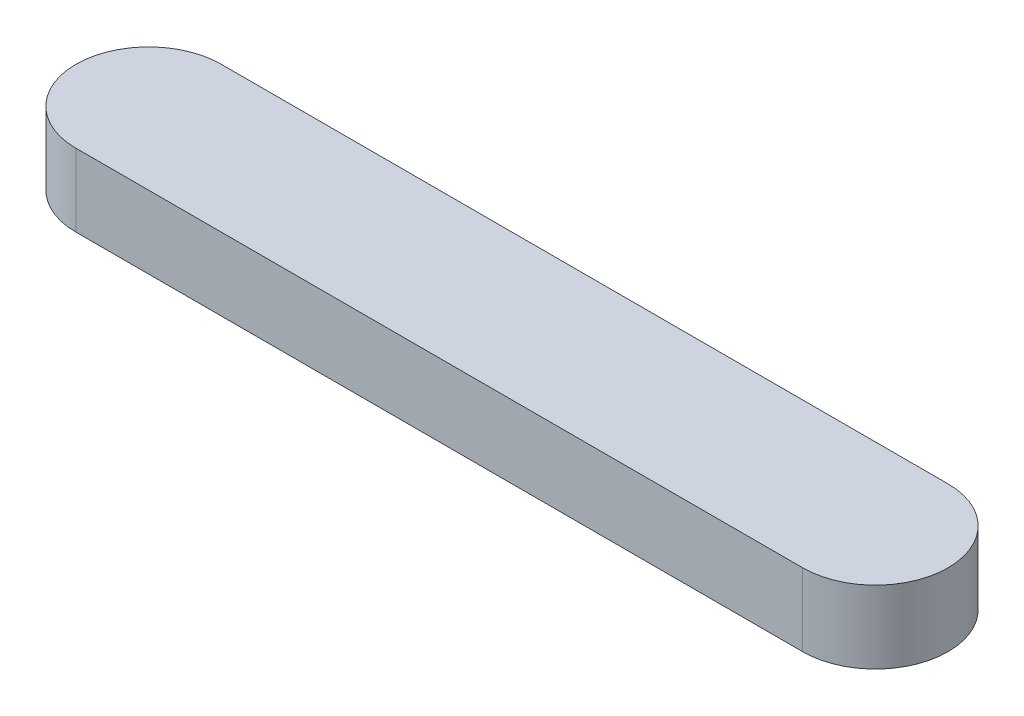
SolidWorks part; units mm, degrees
ref_plane "Front" through (0, 0, 0) normal (0, 0, 1) x (1, 0, 0)
ref_plane "Top" through (0, 0, 0) normal (0, 1, 0) x (1, 0, 0)
ref_plane "Right" through (0, 0, 0) normal (1, 0, 0) x (0, 0, -1)
sketch "Sketch1" plane through (0, 0, 0) normal (0, 1, 0) x (1, 0, 0)
  line L0 (0, 0) -> (25.4, 0) construction
  line L1 (0, 2.54) -> (25.4, 2.54)
  line L2 (0, -2.54) -> (25.4, -2.54)
  arc A2 (0, 2.54) -> (0, -2.54) centre (0, 0) ccw
  arc A3 (25.4, -2.54) -> (25.4, 2.54) centre (25.4, 0) ccw
  point P3 (12.7, 0)
  dimension "D2" = 2.54
  dimension "D1" = 25.4
extrude "Boss-Extrude1" add sketch "Sketch1" along normal blind 2.54
